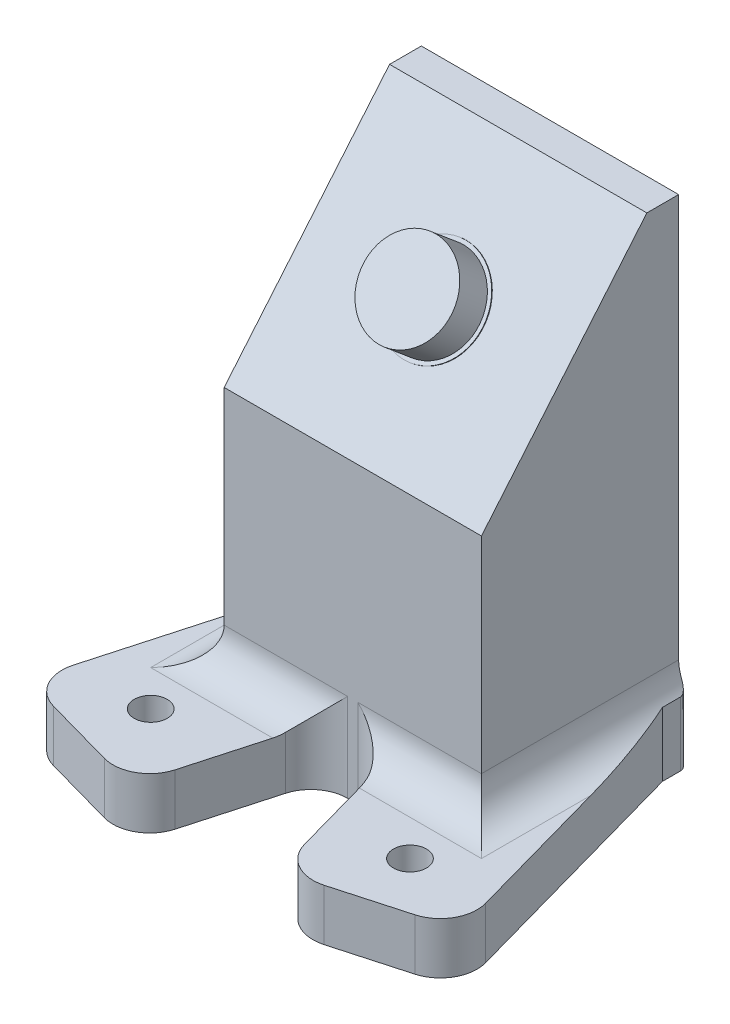
SolidWorks part; units mm, degrees
ref_plane "Ebene vorne" through (0, 0, 0) normal (0, 0, 1) x (1, 0, 0)
ref_plane "Ebene oben" through (0, 0, 0) normal (0, 1, 0) x (1, 0, 0)
ref_plane "Ebene rechts" through (0, 0, 0) normal (1, 0, 0) x (0, 0, -1)
sketch "Skizze1" plane through (0, 0, 0) normal (1, 0, 0) x (0, 0, -1)
  line L0 (0, 0) -> (22.4976, 0)
  line L1 (0, 0) -> (0, 40)
  line L2 (0, 40) -> (22.4976, 66.8116)
  line L3 (22.4976, 66.8116) -> (22.4976, 0) construction
  line L4 (22.4976, 0) -> (26.82, 0)
  line L5 (26.82, 0) -> (26.82, 66.8116)
  line L6 (26.82, 66.8116) -> (22.4976, 66.8116)
  dimension "D1" = 50
  dimension "D2" = 40
  dimension "D3" = 35
  dimension "D4" = 26.82
extrude "Aufsatz-Linear austragen1" add sketch "Skizze1" along normal blind 35
sketch "Skizze3" plane through (0, 16.527, 19.6962) normal (0, 0.6428, 0.766) x (1, 0, 0)
  line L0 (0, 65.6418) -> (35, 30.6418) construction
  line L1 (17.5, 48.1418) -> (35, 65.6418) construction
  line L2 (35, 65.6418) -> (0, 65.6418) construction
  line L3 (35, 65.6418) -> (35, 30.6418) construction
  circle A0 centre (17.5, 48.1418) radius 6
  dimension "D1" = 12
extrude "Aufsatz-Linear austragen2" add sketch "Skizze3" along normal blind 5
sketch "Skizze4" plane through (0, 16.527, 19.6962) normal (0, 0.6428, 0.766) x (1, 0, 0)
  circle A0 centre (17.5, 48.1418) radius 6.5
  dimension "D1" = 13
extrude "Aufsatz-Linear austragen3" add sketch "Skizze4" along normal blind 0.1
ref_plane "Ebene1" through (0, 40, 0) normal (0, -1, 0) x (-1, 0, 0)
ref_plane "Ebene2" through (0, 4.5, 0) normal (0, 1, 0) x (1, 0, 0)
sketch "Skizze7" plane through (0, 4.5, 0) normal (0, -1, 0) x (-1, 0, 0)
  line L0 (-35, 26.82) -> (0, 26.82) construction
  line L1 (-35, 0) -> (0, 26.82) construction
  line L2 (-17.5, 13.41) -> (-17.5, 26.82) construction
  line L4 (-17.5, 13.41) -> (-35, 13.41) construction
  line L5 (-35, 0) -> (-35, 26.82) construction
  circle A0 centre (-28.5, 5) radius 2.85
  circle A1 centre (-6.5, 5) radius 2.85
  circle A2 centre (-6.5, 21.82) radius 2.85
  circle A3 centre (-28.5, 21.82) radius 2.85
  dimension "D1" = 5.7
  dimension "D2" = 11
  dimension "D3" = 5
extrude "Schnitt-Linear austragen1" [suppressed] cut sketch "Skizze7" against normal through all
hole_wizard "Ø3.4 (3.4) Durchmesser Bohrung1" [suppressed] positions "3D-Skizze3" profile "Skizze8" hole size "Ø3.4" standard "DIN"
sketch3d "3D-Skizze3" [suppressed]
  line L0 (6.5, 101.5966, -5) -> (6.5, 4.5, -5) construction
  line L1 (6.5, 118.3109, -21.82) -> (6.5, 4.5, -21.82) construction
  line L2 (28.5, 118.3109, -21.82) -> (28.5, 4.5, -21.82) construction
  line L3 (28.5, 101.5966, -5) -> (28.5, 4.5, -5) construction
  point P0 (6.5, 4.5, -5)
  point P4 (6.5, 4.5, -21.82)
  point P8 (28.5, 4.5, -21.82)
  point P12 (28.5, 4.5, -5)
sketch "Skizze8" plane through (6.5, 4.5, -5) normal (1, 0, 0) x (0, 0, 1)
  line L0 (0, 0) -> (0, 4.5)
  line L1 (0, 4.5) -> (1.7, 4.5)
  line L2 (1.7, 4.5) -> (1.7, 0)
  line L5 (1.7, 0) -> (0, 0)
  line L11 (0, -6.35) -> (0, 107.95) construction
  dimension "Bohrerdurchmesser" = 3.4
  dimension "Bohrungstiefe" = 4.5
sketch "Skizze9" plane through (0, 0, 0) normal (0, -1, 0) x (1, 0, 0)
  circle A0 centre (17.4988, -21.6442) radius 1.425
  dimension "D1" = 2.85
extrude "Schnitt-Linear austragen2" cut sketch "Skizze9" against normal blind 10
sketch "Skizze10" plane through (0, 0, 0) normal (0, -1, 0) x (1, 0, 0)
  line L0 (35, -26.82) -> (36.2227, -26.82)
  line L1 (36.2227, -26.82) -> (36.2227, -23.3967)
  line L2 (36.2227, -23.3967) -> (46.8982, 14.8069)
  line L3 (117.4988, 267.461) -> (36.7609, -21.4705) construction
  line L4 (46.8982, 14.8069) -> (27.6361, 20.1894)
  line L5 (98.2367, 272.8435) -> (17.4988, -16.088) construction
  line L6 (27.6361, 20.1894) -> (21.9944, 0)
  line L7 (35, 0) -> (0, 0) construction
  line L8 (21.9944, 0) -> (35, -26.82)
  line L9 (17.5, 0) -> (17.5, -4.1312) construction
  line L10 (-1.2227, -26.82) -> (-1.2227, -23.3967)
  line L11 (0, -26.82) -> (-1.2227, -26.82)
  line L12 (13.0056, 0) -> (0, -26.82)
  line L13 (-1.2227, -23.3967) -> (-11.8982, 14.8069)
  line L14 (7.3639, 20.1894) -> (13.0056, 0)
  line L15 (-11.8982, 14.8069) -> (7.3639, 20.1894)
  line L16 (25.5016, 12.5508) -> (44.7637, 7.1683) construction
  circle A0 centre (35.1326, 9.8596) radius 2.25
  circle A1 centre (-0.1326, 9.8596) radius 2.25
  dimension "D1" = 4.5
extrude "Aufsatz-Linear austragen4" add sketch "Skizze10" against normal blind 7
fillet "Verrundung1" radius 5 10 edges at (6.5028, 7, 0) (28.4972, 7, 0) (35, 7, -13.41) (0, 7, -13.41) (-11.8982, 3.5, 14.8069) (7.3639, 3.5, 20.1894) (46.8982, 3.5, 14.8069) (27.6361, 3.5, 20.1894) (21.9944, 3.5, 0) (13.0056, 3.5, 0)
fillet "Verrundung2" radius 1 2 edges at (-1.2227, 4.362, -26.82) (36.2227, 4.362, -26.82)
